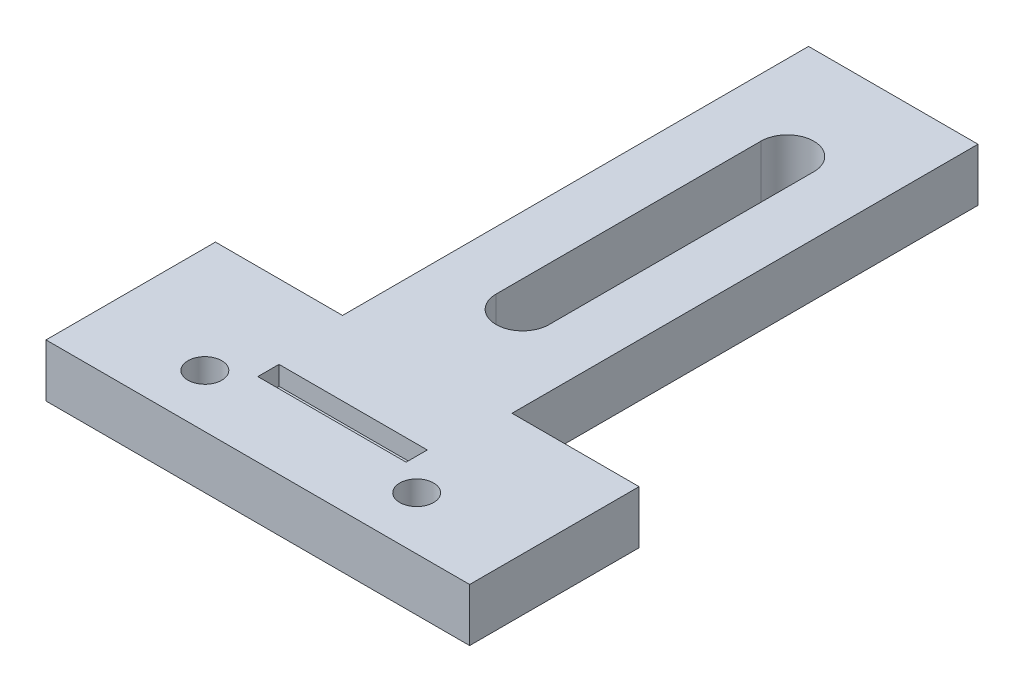
SolidWorks part; units mm, degrees
ref_plane "前视基准面" through (0, 0, 0) normal (0, 0, 1) x (1, 0, 0)
ref_plane "上视基准面" through (0, 0, 0) normal (0, 1, 0) x (1, 0, 0)
ref_plane "右视基准面" through (0, 0, 0) normal (1, 0, 0) x (0, 0, -1)
sketch "草图2" plane through (0, 0, 0) normal (0, 1, 0) x (1, 0, 0)
  line L1 (-20, 16) -> (-8, 16)
  line L2 (-20, 16) -> (-20, 0)
  line L3 (-20, 0) -> (20, 0)
  line L4 (20, 16) -> (20, 0)
  line L5 (0, 60) -> (0, 0) construction
  line L6 (-8, 16) -> (-8, 60)
  line L7 (-10, 3.4) -> (-4.4595, 3.4) construction
  line L9 (-10, 5) -> (-7.5251, 7.4749) construction
  line L12 (8, 16) -> (20, 16)
  line L16 (-8, 60) -> (8, 60)
  line L17 (8, 60) -> (8, 16)
  circle A0 centre (-10, 5) radius 1.6
  circle A1 centre (10, 5) radius 1.6
  circle A2 centre (-10, 5) radius 3.5 construction
  point P14 (0, 60)
  dimension "D2" = 3.2
  dimension "D4" = 40
  dimension "D5" = 45
  dimension "D6" = 7
  dimension "D1" = 20
  dimension "D3" = 55
  dimension "D7" = 5
  dimension "D8" = 16
  dimension "D9" = 11
extrude "凸台-拉伸2" add sketch "草图2" against normal blind 5
sketch "草图5" plane through (0, -5, -9) normal (0, 1, 0) x (1, 0, 0)
  line L0 (0, 41) -> (0, 16) construction
  line L1 (2.5, 41) -> (2.5, 16)
  line L2 (-2.5, 41) -> (-2.5, 16)
  line L4 (-10, -4) -> (10, -4) construction
  arc A0 (2.5, 41) -> (-2.5, 41) centre (0, 41) ccw
  arc A1 (-2.5, 16) -> (2.5, 16) centre (0, 16) ccw
  point P2 (0, 28.5)
  point P14 (0, -4)
  dimension "D1" = 20
  dimension "D2" = 25
  dimension "D3" = 5
extrude "切除-拉伸1" cut sketch "草图5" along normal through all
sketch "草图6" plane through (0, 0, 0) normal (0, 1, 0) x (1, 0, 0)
  line L0 (0, 7) -> (0, 0) construction
  line L1 (-7, 9) -> (7, 9)
  line L2 (-7, 9) -> (-7, 7)
  line L3 (-7, 7) -> (7, 7)
  line L4 (7, 9) -> (7, 7)
  line L5 (-10, 5) -> (10, 5) construction
  dimension "D1" = 2
  dimension "D2" = 4
  dimension "D3" = 14
extrude "切除-拉伸2" cut sketch "草图6" against normal blind 1.8
